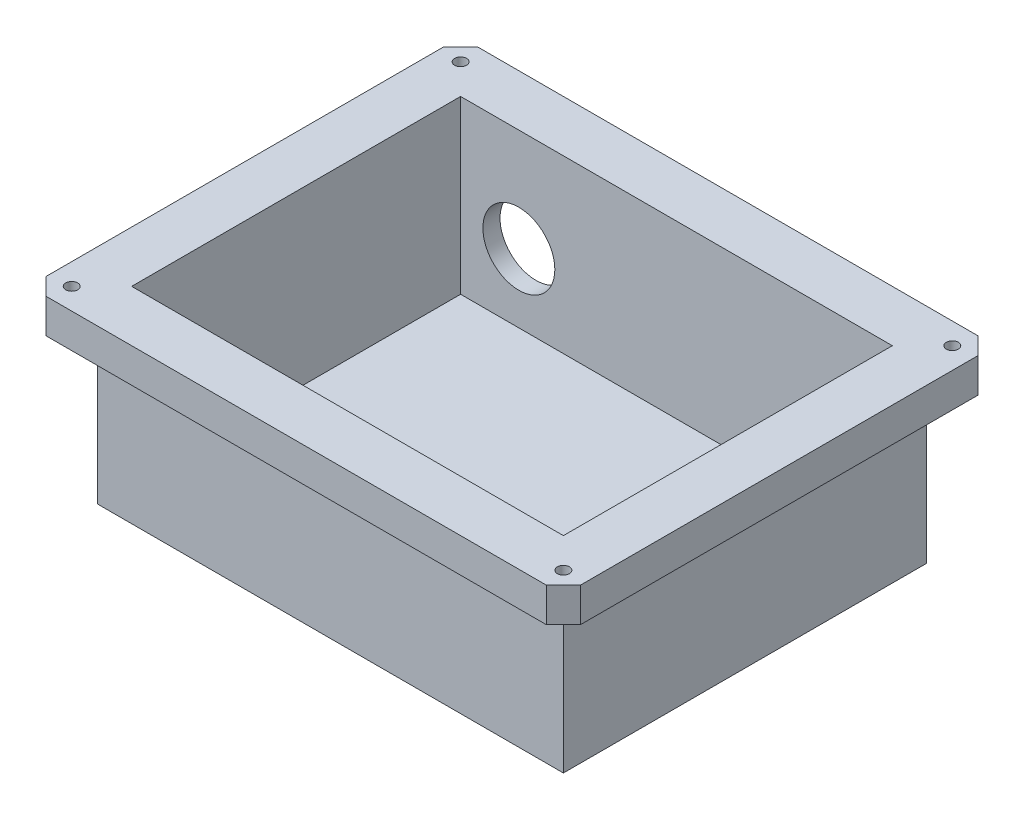
SolidWorks part; units mm, degrees
ref_plane "Front Plane" through (0, 0, 0) normal (0, 0, 1) x (1, 0, 0)
ref_plane "Top Plane" through (0, 0, 0) normal (0, 1, 0) x (1, 0, 0)
ref_plane "Right Plane" through (0, 0, 0) normal (1, 0, 0) x (0, 0, -1)
sketch "Sketch1" plane through (0, 0, 0) normal (0, 1, 0) x (1, 0, 0)
  line L1 (0, -8.6075) -> (126, -8.6075)
  line L2 (0, -8.6075) -> (0, 87.3925)
  line L3 (0, 87.3925) -> (126, 87.3925)
  line L4 (126, -8.6075) -> (126, 87.3925)
  line L5 (-5, -13.6075) -> (131, -13.6075)
  line L6 (-5, -13.6075) -> (-5, 92.3925)
  line L7 (-5, 92.3925) -> (131, 92.3925)
  line L8 (131, -13.6075) -> (131, 92.3925)
  dimension "D1" = 126
  dimension "D2" = 96
  dimension "D3" = 5
  dimension "D4" = 5
  dimension "D5" = 5
  dimension "D6" = 5
extrude "Boss-Extrude1" add sketch "Sketch1" along normal blind 45
sketch "Sketch2" plane through (0, 0, 0) normal (0, -1, 0) x (1, 0, 0)
  line L1 (-5, 13.6075) -> (131, 13.6075)
  line L2 (-5, 13.6075) -> (-5, -92.3925)
  line L3 (-5, -92.3925) -> (131, -92.3925)
  line L4 (131, 13.6075) -> (131, -92.3925)
  point P4 (126, -80.3925)
  point P5 (131, 13.6075)
  point P6 (131, -92.3925)
  point P7 (-5, -92.3925)
extrude "Boss-Extrude3" add sketch "Sketch2" along normal blind 5
sketch "Sketch3" plane through (0, 0, -87.3925) normal (0, 0, 1) x (1, 0, 0)
  line L0 (0, 45) -> (17, 45) construction
  line L1 (17, 45) -> (17, 0) construction
  line L2 (0, 0) -> (0, 20) construction
  line L3 (0, 20) -> (17, 20) construction
  circle A0 centre (17, 20) radius 10.5
  point P7 (17, 20)
  dimension "D3" = 21
  dimension "D1" = 17
  dimension "D2" = 20
extrude "Cut-Extrude1" cut sketch "Sketch3" against normal blind 5
sketch "Sketch4" plane through (0, 45, 0) normal (0, 1, 0) x (1, 0, 0)
  line L0 (-5, 92.3925) -> (-5, -13.6075) construction
  line L1 (-15, 102.3925) -> (141, 102.3925)
  line L2 (-15, 102.3925) -> (-15, -23.6075)
  line L3 (-15, -23.6075) -> (141, -23.6075)
  line L4 (141, 102.3925) -> (141, -23.6075)
  line L5 (-5, -13.6075) -> (131, -13.6075) construction
  line L6 (131, -13.6075) -> (131, 92.3925) construction
  line L7 (131, 92.3925) -> (-5, 92.3925) construction
  line L9 (-5, 92.3925) -> (131, 92.3925)
  line L10 (-5, 92.3925) -> (-5, -13.6075)
  line L11 (-5, -13.6075) -> (131, -13.6075)
  line L12 (131, 92.3925) -> (131, -13.6075)
  dimension "D1" = 10
  dimension "D2" = 10
  dimension "D3" = 10
  dimension "D4" = 10
extrude "Boss-Extrude4" add sketch "Sketch4" along normal blind 5 and the other way blind 5
sketch "Sketch5" plane through (0, 45, 0) normal (0, 1, 0) x (1, 0, 0)
  line L1 (-5, 92.3925) -> (131, 92.3925)
  line L2 (-5, 92.3925) -> (-5, -13.6075)
  line L3 (-5, -13.6075) -> (131, -13.6075)
  line L4 (131, 92.3925) -> (131, -13.6075)
  line L5 (0, 87.3925) -> (126, 87.3925)
  line L6 (0, 87.3925) -> (0, -8.6075)
  line L7 (0, -8.6075) -> (126, -8.6075)
  line L8 (126, 87.3925) -> (126, -8.6075)
extrude "Boss-Extrude6" add sketch "Sketch5" along normal up to surface (5 mm away) up to face at (63, 50, -39.3925)
chamfer "Chamfer1" distance 5 angle 45 4 edges at (-15, 45, -102.3925) (141, 45, -102.3925) (141, 45, 23.6075) (-15, 45, 23.6075)
sketch "Sketch6" plane through (0, 40, 0) normal (0, -1, 0) x (1, 0, 0)
  line L0 (-5, 13.6075) -> (-12.5, 21.1075) construction
  line L1 (-5, 13.6075) -> (-5, 23.6075) construction
  line L2 (-5, 13.6075) -> (63, 13.6075) construction
  line L3 (63, 13.6075) -> (63, -92.3925) construction
  line L4 (63, -92.3925) -> (63, -39.3925) construction
  line L5 (63, -39.3925) -> (-5, -39.3925) construction
  circle A0 centre (-8.75, 17.3575) radius 1.75
  circle A1 centre (-8.75, -96.1425) radius 1.75
  circle A2 centre (134.75, -96.1425) radius 1.75
  circle A3 centre (134.75, 17.3575) radius 1.75
  dimension "D1" = 3.5
  dimension "D2" = 45
extrude "Cut-Extrude2" cut sketch "Sketch6" against normal through all contours A3 | A2 | A0 | A1
